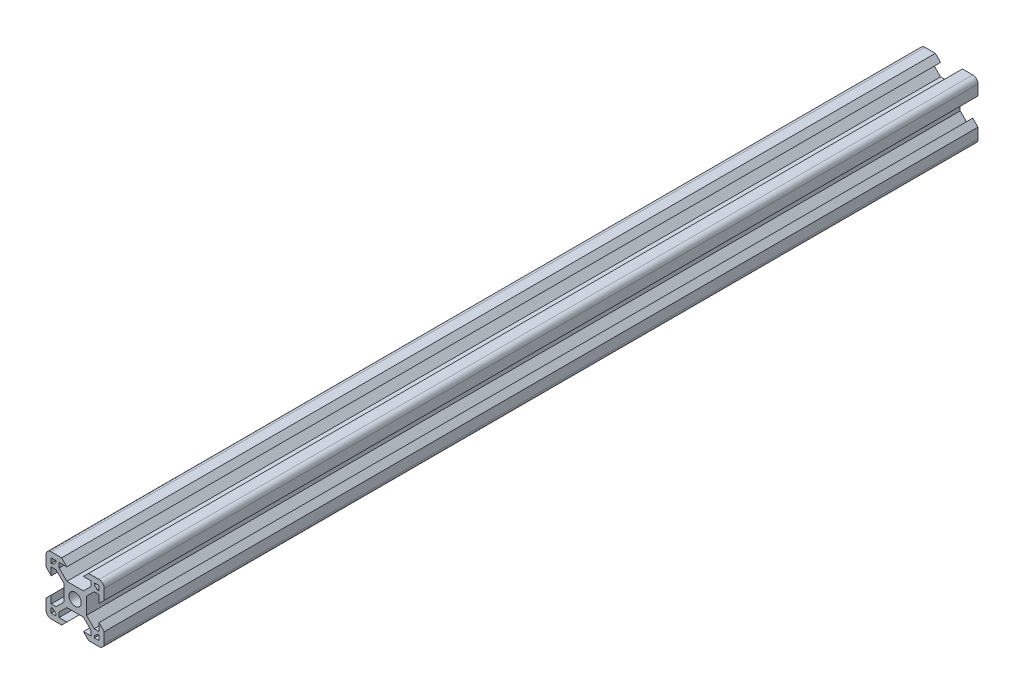
SolidWorks part; units mm, degrees
material "5052-H38, Barre (SS)"
ref_plane "Plan de face" through (0, 0, 0) normal (0, 0, 1) x (1, 0, 0)
ref_plane "Plan de dessus" through (0, 0, 0) normal (0, 1, 0) x (1, 0, 0)
ref_plane "Plan de droite" through (0, 0, 0) normal (1, 0, 0) x (0, 0, -1)
sketch "Esquisse1" plane through (0, 0, 0) normal (0, 0, 1) x (1, 0, 0)
  line L0 (-3.9007, 0) -> (-3.9007, -2.84)
  line L1 (-3.9007, -2.84) -> (-6.56, -5.4993)
  line L2 (-6.56, -5.4993) -> (-8.2, -5.4993)
  line L3 (-8.2, -5.4993) -> (-8.2, -2.84)
  line L4 (-8.2, -2.84) -> (-10, -4.64)
  line L5 (-10, -4.64) -> (-10, -8.2)
  line L6 (0, 0) -> (-17.0509, -17.0509) construction
  line L7 (0, 0) -> (0, -17.0509) construction
  line L8 (0, 0) -> (-30.3777, 0) construction
  line L9 (-4.64, -10) -> (-8.2, -10)
  line L10 (-2.84, -8.2) -> (-4.64, -10)
  line L11 (-5.4993, -8.2) -> (-2.84, -8.2)
  line L12 (-5.4993, -6.56) -> (-5.4993, -8.2)
  line L13 (-2.84, -3.9007) -> (-5.4993, -6.56)
  line L14 (0, -3.9007) -> (-2.84, -3.9007)
  line L15 (-8.2, -8.2) -> (-8.2, -6.5693)
  line L16 (-8.2, -6.5693) -> (-7.63, -6.5693)
  line L17 (-7.63, -6.5693) -> (-6.5693, -7.63)
  line L18 (-6.5693, -7.63) -> (-6.5693, -8.2)
  line L19 (-6.5693, -8.2) -> (-8.2, -8.2)
  line L20 (-3.9007, 0) -> (-3.9007, 2.84)
  line L21 (-3.9007, 2.84) -> (-6.56, 5.4993)
  line L22 (-6.56, 5.4993) -> (-8.2, 5.4993)
  line L23 (-8.2, 5.4993) -> (-8.2, 2.84)
  line L24 (-8.2, 2.84) -> (-10, 4.64)
  line L25 (-10, 4.64) -> (-10, 8.2)
  line L26 (-4.64, 10) -> (-8.2, 10)
  line L27 (-2.84, 8.2) -> (-4.64, 10)
  line L28 (-5.4993, 8.2) -> (-2.84, 8.2)
  line L29 (-5.4993, 6.56) -> (-5.4993, 8.2)
  line L30 (-2.84, 3.9007) -> (-5.4993, 6.56)
  line L31 (0, 3.9007) -> (-2.84, 3.9007)
  line L32 (-8.2, 6.5693) -> (-8.2, 8.2)
  line L33 (-8.2, 8.2) -> (-6.5693, 8.2)
  line L34 (-6.5693, 8.2) -> (-6.5693, 7.63)
  line L35 (-6.5693, 7.63) -> (-7.63, 6.5693)
  line L36 (-7.63, 6.5693) -> (-8.2, 6.5693)
  line L37 (0, 3.9007) -> (2.84, 3.9007)
  line L38 (2.84, 3.9007) -> (5.4993, 6.56)
  line L39 (5.4993, 6.56) -> (5.4993, 8.2)
  line L40 (5.4993, 8.2) -> (2.84, 8.2)
  line L41 (2.84, 8.2) -> (4.64, 10)
  line L42 (4.64, 10) -> (8.2, 10)
  line L43 (10, 4.64) -> (10, 8.2)
  line L44 (8.2, 2.84) -> (10, 4.64)
  line L45 (8.2, 5.4993) -> (8.2, 2.84)
  line L46 (6.56, 5.4993) -> (8.2, 5.4993)
  line L47 (3.9007, 2.84) -> (6.56, 5.4993)
  line L48 (3.9007, 0) -> (3.9007, 2.84)
  line L49 (6.5693, 8.2) -> (8.2, 8.2)
  line L50 (8.2, 8.2) -> (8.2, 6.5693)
  line L51 (8.2, 6.5693) -> (7.63, 6.5693)
  line L52 (7.63, 6.5693) -> (6.5693, 7.63)
  line L53 (6.5693, 7.63) -> (6.5693, 8.2)
  line L54 (3.9007, 0) -> (3.9007, -2.84)
  line L55 (3.9007, -2.84) -> (6.56, -5.4993)
  line L56 (6.56, -5.4993) -> (8.2, -5.4993)
  line L57 (8.2, -5.4993) -> (8.2, -2.84)
  line L58 (8.2, -2.84) -> (10, -4.64)
  line L59 (10, -4.64) -> (10, -8.2)
  line L60 (4.64, -10) -> (8.2, -10)
  line L61 (2.84, -8.2) -> (4.64, -10)
  line L62 (5.4993, -8.2) -> (2.84, -8.2)
  line L63 (5.4993, -6.56) -> (5.4993, -8.2)
  line L64 (2.84, -3.9007) -> (5.4993, -6.56)
  line L65 (0, -3.9007) -> (2.84, -3.9007)
  line L66 (8.2, -6.5693) -> (8.2, -8.2)
  line L67 (8.2, -8.2) -> (6.5693, -8.2)
  line L68 (6.5693, -8.2) -> (6.5693, -7.63)
  line L69 (6.5693, -7.63) -> (7.63, -6.5693)
  line L70 (7.63, -6.5693) -> (8.2, -6.5693)
  circle A0 centre (0, 0) radius 2.1
  arc A1 (-10, -8.2) -> (-8.2, -10) centre (-8.2, -8.2) ccw
  arc A2 (-8.2, 10) -> (-10, 8.2) centre (-8.2, 8.2) ccw
  arc A3 (10, 8.2) -> (8.2, 10) centre (8.2, 8.2) ccw
  arc A4 (8.2, -10) -> (10, -8.2) centre (8.2, -8.2) ccw
  point P23 (-7.0997, -7.0997)
  dimension "D4" = 4.2
  dimension "D1" = 45
  dimension "D2" = 5.68
  dimension "D3" = 1.64
  dimension "D5" = 1.5
  dimension "D6" = 20
  dimension "D7" = 1.8
  dimension "D8" = 1.07
  dimension "D9" = 4
extrude "Boss.-Extru.2" add sketch "Esquisse1" along normal mid plane 300
